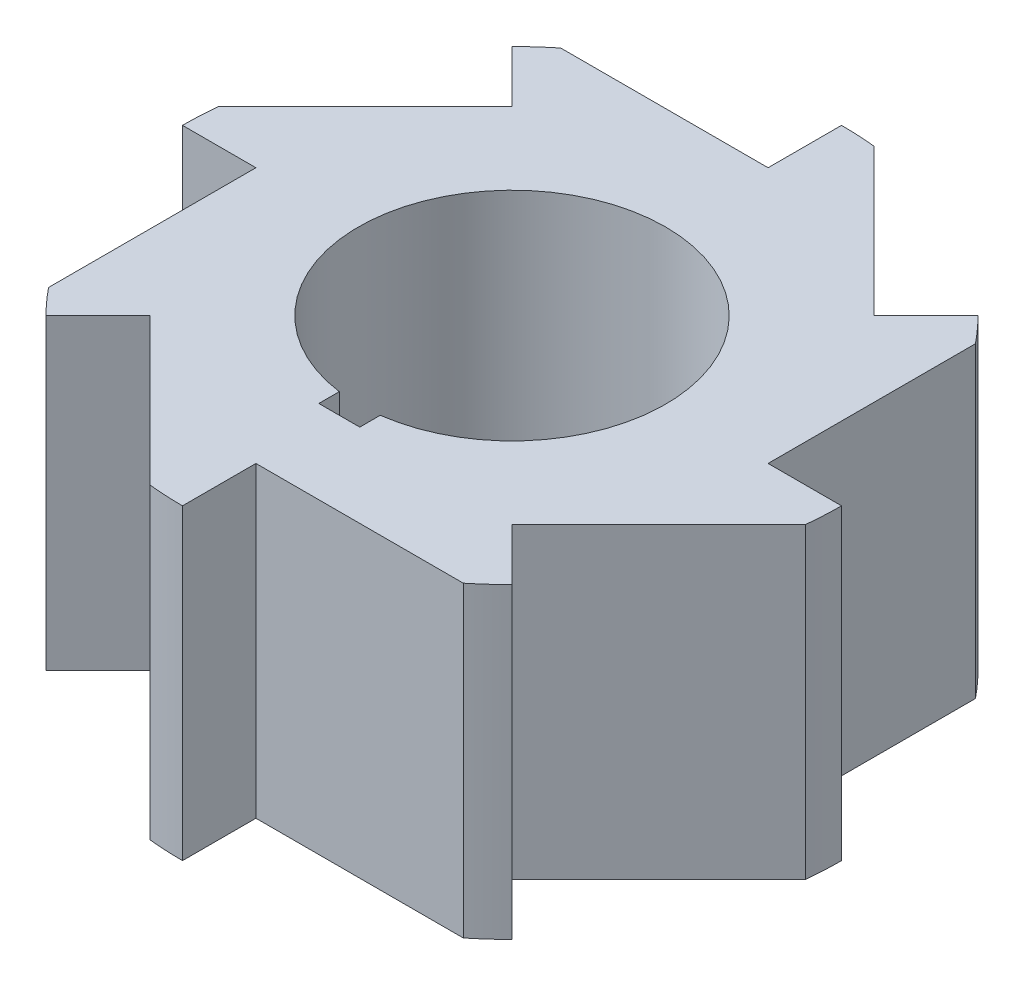
SolidWorks part; units mm, degrees
ref_plane "Front Plane" through (0, 0, 0) normal (0, 0, 1) x (1, 0, 0)
ref_plane "Top Plane" through (0, 0, 0) normal (0, 1, 0) x (1, 0, 0)
ref_plane "Right Plane" through (0, 0, 0) normal (1, 0, 0) x (0, 0, -1)
sketch "Sketch1" plane through (0, 0, 0) normal (0, 1, 0) x (1, 0, 0)
  line L4 (0, -25) -> (0, -32.1683)
  line L5 (-3.3633, -31.992) -> (-17.6777, -17.6777)
  line L6 (-25, -20.2435) -> (-25, 0)
  line L7 (-17.6777, -17.6777) -> (-22.7464, -22.7464)
  line L8 (-31.992, 3.3633) -> (-17.6777, 17.6777)
  line L9 (-25, 0) -> (-32.1683, 0)
  line L10 (-20.2435, 25) -> (0, 25)
  line L11 (-17.6777, 17.6777) -> (-22.7464, 22.7464)
  line L12 (3.3633, 31.992) -> (17.6777, 17.6777)
  line L13 (0, 25) -> (0, 32.1683)
  line L14 (25, 20.2435) -> (25, 0)
  line L15 (17.6777, 17.6777) -> (22.7464, 22.7464)
  line L16 (31.992, -3.3633) -> (17.6777, -17.6777)
  line L17 (25, 0) -> (32.1683, 0)
  line L18 (20.2435, -25) -> (0, -25)
  line L19 (17.6777, -17.6777) -> (22.7464, -22.7464)
  line L20 (-2, -16.8607) -> (-2, -14.8607)
  line L21 (2, -16.8607) -> (2, -14.8607)
  line L22 (-2, -16.8607) -> (2, -16.8607)
  arc A1 (2, -14.8607) -> (-2, -14.8607) centre (0, 0) ccw
  arc A2 (20.2435, -25) -> (22.7464, -22.7464) centre (0, 0) ccw
  arc A3 (-3.3633, -31.992) -> (0, -32.1683) centre (0, 0) ccw
  arc A4 (-25, -20.2435) -> (-22.7464, -22.7464) centre (0, 0) ccw
  arc A5 (-31.992, 3.3633) -> (-32.1683, 0) centre (0, 0) ccw
  arc A6 (-20.2435, 25) -> (-22.7464, 22.7464) centre (0, 0) ccw
  arc A7 (3.3633, 31.992) -> (0, 32.1683) centre (0, 0) ccw
  arc A8 (25, 20.2435) -> (22.7464, 22.7464) centre (0, 0) ccw
  arc A9 (31.992, -3.3633) -> (32.1683, 0) centre (0, 0) ccw
  point P30 (0, 0)
  dimension "D1" = 8
  dimension "D2" = 2
  dimension "D3" = 2
extrude "Boss-Extrude3" add sketch "Sketch1" along normal blind 30
